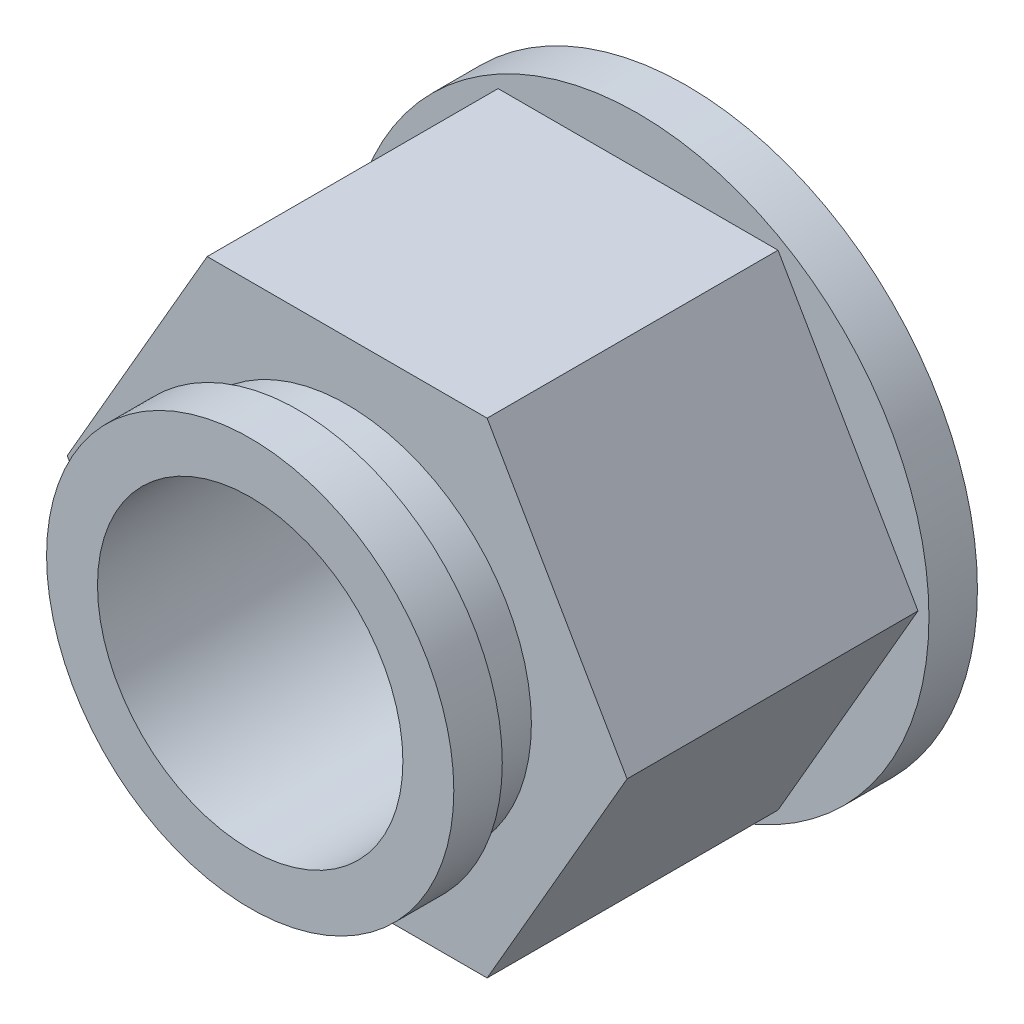
SolidWorks part; units mm, degrees
ref_plane "Plan de face" through (0, 0, 0) normal (0, 0, 1) x (1, 0, 0)
ref_plane "Plan de dessus" through (0, 0, 0) normal (0, 1, 0) x (1, 0, 0)
ref_plane "Plan de droite" through (0, 0, 0) normal (1, 0, 0) x (0, 0, -1)
sketch "Esquisse1" plane through (0, 0, 0) normal (0, 0, 1) x (1, 0, 0)
  line L1 (7.3323, 0) -> (3.6662, 6.35)
  line L2 (3.6662, 6.35) -> (-3.6662, 6.35)
  line L3 (-3.6662, 6.35) -> (-7.3323, 0)
  line L4 (-7.3323, 0) -> (-3.6662, -6.35)
  line L5 (-3.6662, -6.35) -> (3.6662, -6.35)
  line L6 (3.6662, -6.35) -> (7.3323, 0)
  circle A0 centre (0, 0) radius 6.35 construction
  dimension "D1" = 12.7
extrude "Boss.-Extru.1" add sketch "Esquisse1" along normal mid plane 7.62
sketch "Esquisse2" plane through (0, 0, -3.81) normal (0, 0, -1) x (-1, 0, 0)
  circle A0 centre (0, 0) radius 7.62
  dimension "D1" = 15.24
extrude "Boss.-Extru.2" add sketch "Esquisse2" along normal blind 1.27
sketch "Esquisse3" plane through (0, 0, 3.81) normal (0, 0, 1) x (1, 0, 0)
  circle A0 centre (0, 0) radius 4.826
  dimension "D1" = 9.652
extrude "Boss.-Extru.3" add sketch "Esquisse3" along normal blind 1.27
sketch "Esquisse4" plane through (0, 0, 5.08) normal (0, 0, 1) x (1, 0, 0)
  circle A0 centre (0, 0) radius 5.334
  dimension "D1" = 10.668
extrude "Boss.-Extru.4" add sketch "Esquisse4" along normal blind 1.27
sketch "Esquisse5" plane through (0, 0, -5.08) normal (0, 0, -1) x (-1, 0, 0)
  circle A0 centre (0, 0) radius 4
  dimension "D1" = 8
extrude "Enlèv. mat.-Extru.1" cut sketch "Esquisse5" against normal through all
